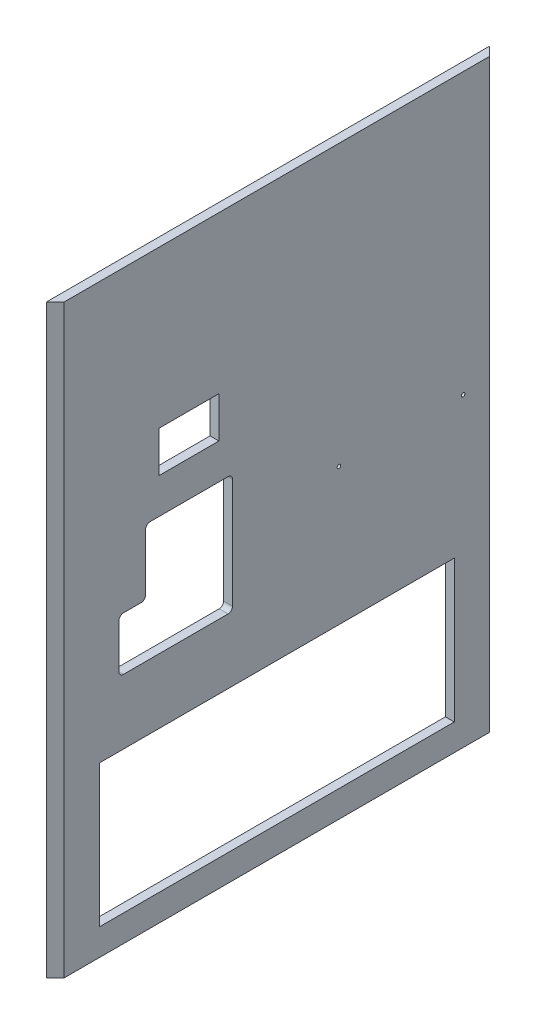
SolidWorks part; units mm, degrees
material "ABS"
ref_plane "Alzado" through (0, 0, 0) normal (0, 0, 1) x (1, 0, 0)
ref_plane "Planta" through (0, 0, 0) normal (0, 1, 0) x (1, 0, 0)
ref_plane "Vista lateral" through (0, 0, 0) normal (1, 0, 0) x (0, 0, -1)
sketch "Croquis1" plane through (0, 0, 0) normal (0, 1, 0) x (1, 0, 0)
  line L0 (0, 0) -> (0, 250)
  line L1 (0, 250) -> (-5, 250)
  line L2 (-5, 250) -> (-5, 0)
  line L3 (-5, 0) -> (0, 0)
  dimension "D1" = 250
  dimension "D2" = 250
  dimension "D3" = 5
extrude "Saliente-Extruir1" add sketch "Croquis1" along normal blind 330
sketch "Croquis2" plane through (0, 330, 0) normal (0, 1, 0) x (1, 0, 0)
  line L0 (0, 250) -> (0, 245)
  line L1 (0, 0) -> (0, 250) construction
  line L2 (0, 245) -> (-5, 250)
  line L3 (-5, 250) -> (0, 250)
  line L4 (-5, 0) -> (0, 5)
  line L5 (0, 5) -> (0, 0)
  line L6 (0, 0) -> (-5, 0)
  dimension "D1" = 5
  dimension "D2" = 5
extrude "Cortar-Extruir1" cut sketch "Croquis2" against normal up to next
sketch "Croquis3" plane through (-5, 0, 0) normal (-1, 0, 0) x (0, 0, 1)
  line L0 (-225, 15) -> (-225, 95)
  line L1 (-225, 95) -> (-25, 95)
  line L2 (-25, 95) -> (-25, 15)
  line L3 (-25, 15) -> (-225, 15)
  line L4 (-250, 0) -> (0, 0) construction
  line L5 (0, 330) -> (0, 0) construction
  dimension "D1" = 80
  dimension "D2" = 200
  dimension "D3" = 15
  dimension "D4" = 25
extrude "Cortar-Extruir2" cut sketch "Croquis3" against normal up to next
sketch "Croquis4" plane through (-5, 0, 0) normal (-1, 0, 0) x (0, 0, 1)
  line L0 (-250, 165) -> (-100, 165) construction
  line L1 (-250, 330) -> (-250, 0) construction
  line L2 (-100, 198.5) -> (-100, 131.5)
  line L3 (-100, 131.5) -> (-51, 131.5)
  line L4 (-100, 198.5) -> (-51, 198.5)
  line L8 (-51, 131.5) -> (-36, 131.5)
  line L9 (-36, 131.5) -> (-36, 161.5)
  line L10 (-36, 161.5) -> (-51, 161.5)
  line L11 (-51, 198.5) -> (-51, 161.5)
  point P7 (-100, 165)
  dimension "D1" = 150
  dimension "D2" = 67
  dimension "D4" = 49
  dimension "D6" = 15
extrude "Cortar-Extruir3" cut sketch "Croquis4" against normal through all
fillet "Redondeo1" radius 2.5 6 edges at (-2.5, 131.5, -100) (-2.5, 198.5, -100) (-2.5, 198.5, -51) (-2.5, 161.5, -51) (-2.5, 161.5, -36) (-2.5, 131.5, -36)
sketch "Croquis5" plane through (-5, 0, 0) normal (-1, 0, 0) x (0, 0, 1)
  line L0 (-75.5, 198.5) -> (-75.5, 218.5) construction
  line L1 (-53.5, 198.5) -> (-97.5, 198.5) construction
  line L2 (-92.35, 218.5) -> (-58.65, 218.5)
  line L3 (-58.65, 218.5) -> (-58.65, 241.6)
  line L4 (-58.65, 241.6) -> (-92.35, 241.6)
  line L5 (-92.35, 241.6) -> (-92.35, 218.5)
  point P7 (-75.5, 218.5)
  dimension "D1" = 20
  dimension "D2" = 33.7
  dimension "D3" = 23.1
extrude "Cortar-Extruir4" cut sketch "Croquis5" against normal through all
sketch "Croquis6" plane through (-5, 0, 0) normal (-1, 0, 0) x (0, 0, 1)
  line L0 (-250, 330) -> (-250, 0) construction
  line L1 (-250, 0) -> (0, 0) construction
  circle A0 centre (-230, 172.2) radius 1
  circle A1 centre (-160, 172.2) radius 1
  dimension "D1" = 2
  dimension "D2" = 2
  dimension "D3" = 70
  dimension "D4" = 20
  dimension "D5" = 172.2
extrude "Cortar-Extruir5" cut sketch "Croquis6" against normal up to next
